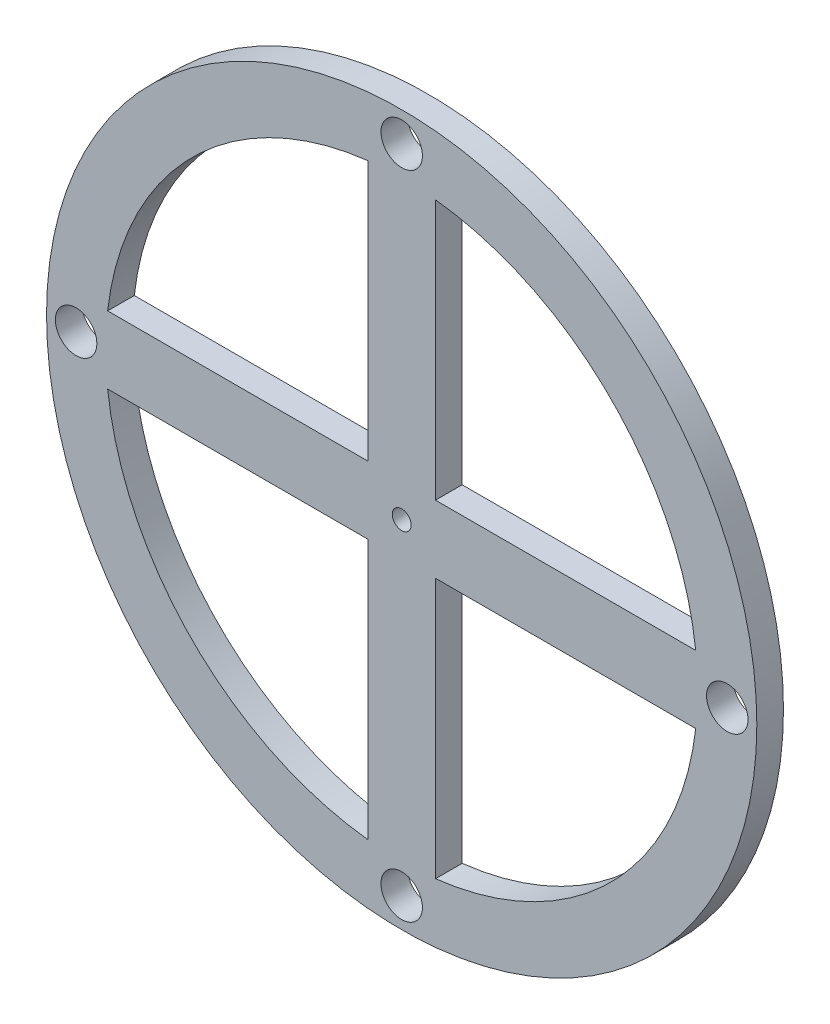
SolidWorks part; units mm, degrees
ref_plane "Plan de face" through (0, 0, 0) normal (0, 0, 1) x (1, 0, 0)
ref_plane "Plan de dessus" through (0, 0, 0) normal (0, 1, 0) x (1, 0, 0)
ref_plane "Plan de droite" through (0, 0, 0) normal (1, 0, 0) x (0, 0, -1)
sketch "Esquisse1" plane through (0, 0, 0) normal (0, 0, 1) x (1, 0, 0)
  line L0 (50, 0) -> (60, 0) construction
  line L2 (5.7143, 49.6724) -> (5.7143, 5.7143)
  line L4 (-5.7143, 49.6724) -> (-5.7143, 5.7143)
  line L5 (0, 0) -> (0, 12.222) construction
  line L6 (0, -50) -> (0, -60) construction
  line L7 (-49.6724, 5.7143) -> (-5.7143, 5.7143)
  line L9 (-49.6724, -5.7143) -> (-5.7143, -5.7143)
  line L11 (0, 0) -> (12.4869, 0) construction
  line L13 (5.7143, 5.7143) -> (49.6724, 5.7143)
  line L14 (5.7143, -5.7143) -> (49.6724, -5.7143)
  line L16 (-5.7143, -5.7143) -> (-5.7143, -49.6724)
  line L18 (5.7143, -5.7143) -> (5.7143, -49.6724)
  circle A0 centre (0, 0) radius 60
  circle A1 centre (0, 0) radius 50
  circle A2 centre (0, 0) radius 1.595
  circle A11 centre (0, -55) radius 3.5
  circle A12 centre (55, 0) radius 3.5
  circle A13 centre (-55, 0) radius 3.5
  circle A14 centre (0, 55) radius 3.5
  dimension "D1" = 120
  dimension "D2" = 100
  dimension "D3" = 3.19
  dimension "D4" = 7
  dimension "D5" = 7
extrude "Boss.-Extru.4" add sketch "Esquisse1" along normal blind 4.5 contours A0 A13 A12 A11 A1 A14 | L2 A1 L4 L7 L9 L16 L18 L14 L13 A2
